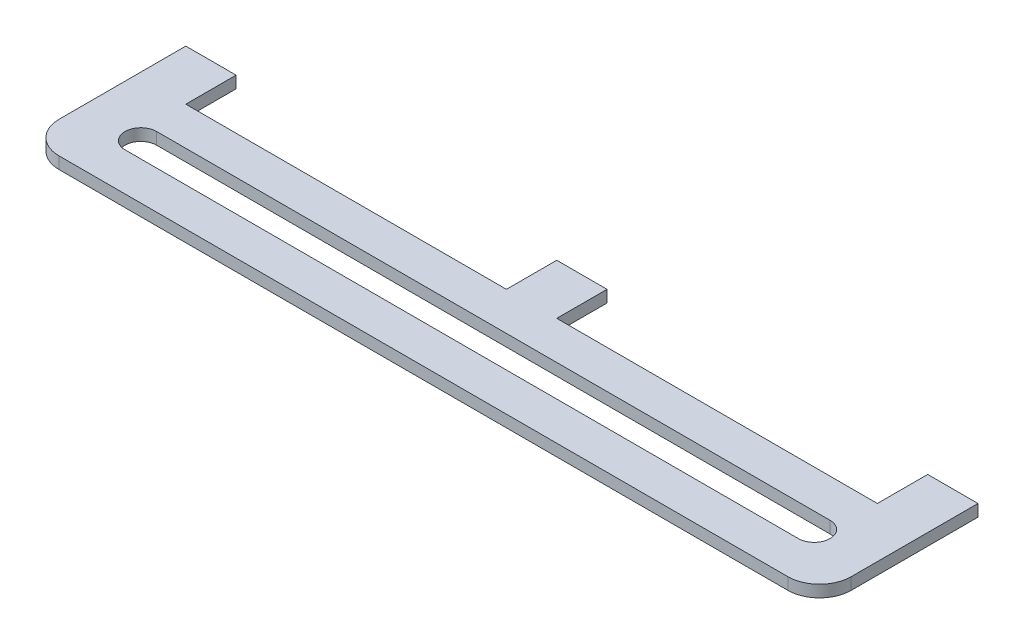
SolidWorks part; units mm, degrees
ref_plane "Front Plane" through (0, 0, 0) normal (0, 0, 1) x (1, 0, 0)
ref_plane "Top Plane" through (0, 0, 0) normal (0, 1, 0) x (1, 0, 0)
ref_plane "Right Plane" through (0, 0, 0) normal (1, 0, 0) x (0, 0, -1)
sketch "Sketch1" plane through (0, 0, 0) normal (0, 1, 0) x (1, 0, 0)
  line L0 (-85, -6.35) -> (85, -6.35) construction
  line L1 (92, -20) -> (-92, -20)
  line L2 (100, -12) -> (100, 20)
  line L3 (100, 20) -> (87.3, 20)
  line L4 (-100, -12) -> (-100, 20)
  line L5 (100, -20) -> (-100, 20) construction
  line L6 (100, 20) -> (-100, -20) construction
  line L9 (-85, -2.35) -> (85, -2.35)
  line L10 (-6.35, 20) -> (6.35, 20)
  line L11 (-87.3, 20) -> (-87.3, 7.3)
  line L12 (-87.3, 7.3) -> (87.3, 7.3)
  line L13 (87.3, 20) -> (87.3, 7.3)
  line L14 (-85, -10.35) -> (85, -10.35)
  line L15 (0, -2.35) -> (0, 7.3) construction
  line L16 (0, -10.35) -> (0, -20) construction
  line L17 (-87.3, 20) -> (-100, 20)
  line L18 (-6.35, 20) -> (6.35, 20)
  line L19 (-6.35, 20) -> (-6.35, 7.3)
  line L20 (-6.35, 7.3) -> (6.35, 7.3)
  line L21 (6.35, 20) -> (6.35, 7.3)
  line L22 (6.35, 20) -> (-6.35, 20)
  arc A2 (-85, -2.35) -> (-85, -10.35) centre (-85, -6.35) ccw
  arc A3 (85, -10.35) -> (85, -2.35) centre (85, -6.35) ccw
  arc A4 (100, -12) -> (92, -20) centre (92, -12) cw
  arc A5 (-92, -20) -> (-100, -12) centre (-92, -12) cw
  point P0 (0, 0)
  point P8 (0, -6.35)
  point P33 (0, 7.3)
  dimension "D6" = 8
  dimension "D8" = 8
  dimension "D1" = 200
  dimension "D2" = 40
  dimension "D3" = 12.7
  dimension "D4" = 170
  dimension "D5" = 12.7
  dimension "D7" = 12.7
extrude "Boss-Extrude1" add sketch "Sketch1" along normal blind 3 contours A5 L1 A4 L2 L3 L13 L12 L11 L17 L4 A3 L14 A2 L9 | L21 L10 L19 L12
